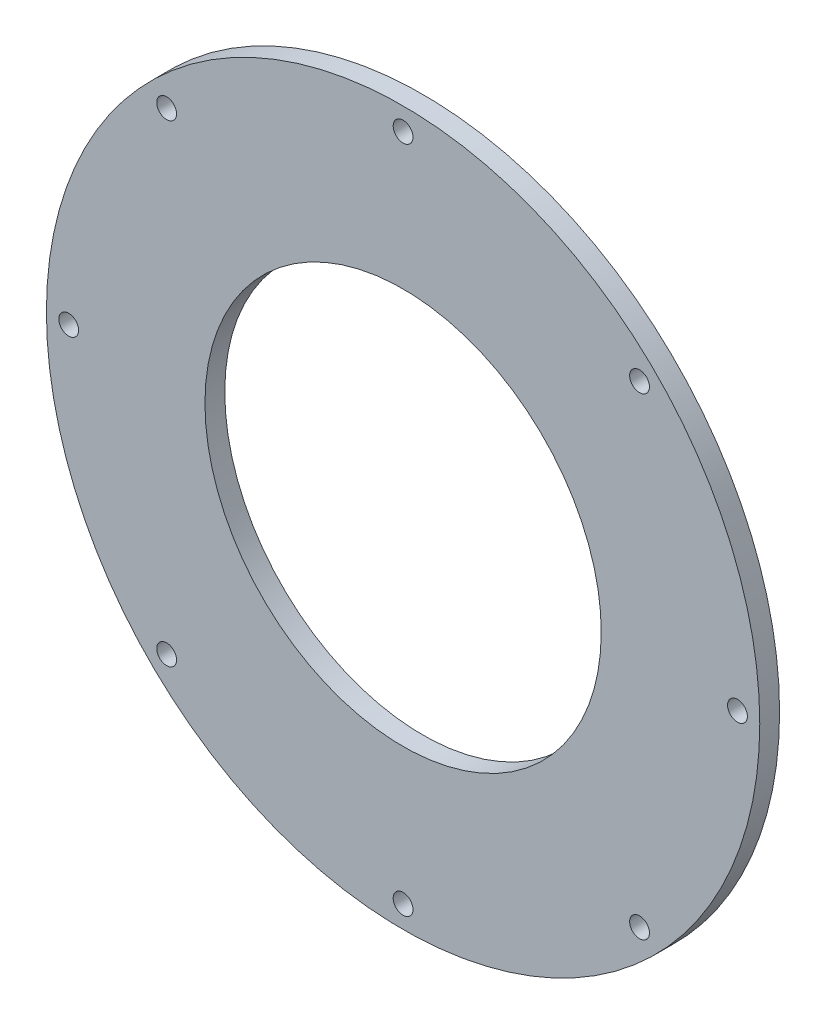
SolidWorks part; units mm, degrees
ref_plane "前视基准面" through (0, 0, 0) normal (0, 0, 1) x (1, 0, 0)
ref_plane "上视基准面" through (0, 0, 0) normal (0, 1, 0) x (1, 0, 0)
ref_plane "右视基准面" through (0, 0, 0) normal (1, 0, 0) x (0, 0, -1)
sketch "草图1" plane through (0, 0, 0) normal (0, 0, 1) x (1, 0, 0)
  line L0 (0, -52.5) -> (0, -72) construction
  circle A0 centre (0, 0) radius 40
  circle A1 centre (0, 0) radius 72
  circle A3 centre (0, 0) radius 52.5 construction
  circle A4 centre (0, -67.5) radius 2
  circle A5 centre (0, -67.5) radius 3.8 construction
  circle A6 centre (-47.7297, -47.7297) radius 2
  circle A7 centre (-67.5, 0) radius 2
  circle A8 centre (-47.7297, 47.7297) radius 2
  circle A9 centre (0, 67.5) radius 2
  circle A10 centre (47.7297, 47.7297) radius 2
  circle A11 centre (67.5, 0) radius 2
  circle A12 centre (47.7297, -47.7297) radius 2
  dimension "D1" = 80
  dimension "D2" = 144
  dimension "D3" = 105
  dimension "D4" = 7.6
  dimension "D6" = 4.5
  dimension "D5" = 8
extrude "凸台-拉伸1" add sketch "草图1" along normal blind 4
